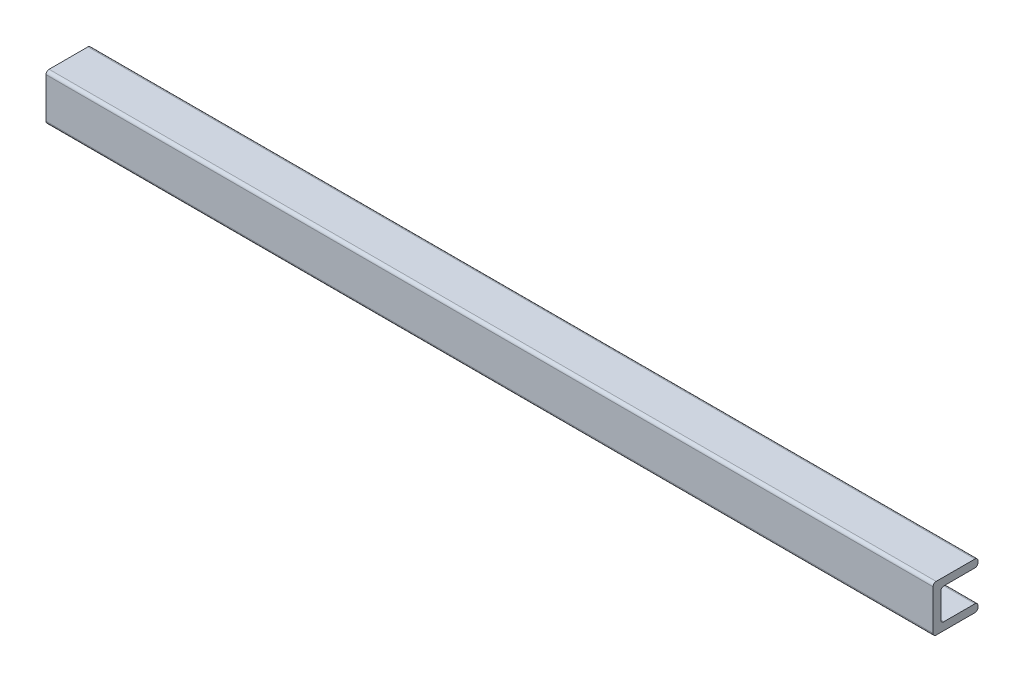
SolidWorks part; units mm, degrees
material "1023 Carbon Steel Sheet (SS)"
ref_plane "Ön Düzlem" through (0, 0, 0) normal (0, 0, 1) x (1, 0, 0)
ref_plane "Üst Düzlem" through (0, 0, 0) normal (0, 1, 0) x (1, 0, 0)
ref_plane "Sağ Düzlem" through (0, 0, 0) normal (1, 0, 0) x (0, 0, -1)
sketch "Sketch1" plane through (0, 0, 0) normal (1, 0, 0) x (0, 0, -1)
  line L0 (-168, 10) -> (-188, 10)
  line L1 (-190, 8) -> (-190, -8)
  line L2 (-188, -10) -> (-168, -10)
  line L3 (-168, 15) -> (-193, 15)
  line L4 (-195, 13) -> (-195, -13)
  line L5 (-193, -15) -> (-168, -15)
  line L6 (-166, 13) -> (-166, 12)
  line L7 (-166, -12) -> (-166, -13)
  line L8 (-177.3019, 10) -> (-190, 10) construction
  line L9 (-195, 15) -> (-195, -15) construction
  line L10 (-195, -15) -> (-166, -15) construction
  line L11 (-190, 10) -> (-190, -10) construction
  line L12 (-190, -10) -> (-166, -10) construction
  line L13 (-177.3019, 15) -> (-195, 15) construction
  arc A0 (-168, 10) -> (-166, 12) centre (-168, 12) ccw
  arc A1 (-195, -13) -> (-193, -15) centre (-193, -13) ccw
  arc A2 (-188, 10) -> (-190, 8) centre (-188, 8) ccw
  arc A3 (-190, -8) -> (-188, -10) centre (-188, -8) ccw
  arc A4 (-168, -10) -> (-166, -12) centre (-168, -12) cw
  arc A5 (-168, -15) -> (-166, -13) centre (-168, -13) ccw
  arc A6 (-168, 15) -> (-166, 13) centre (-168, 13) cw
  arc A7 (-193, 15) -> (-195, 13) centre (-193, 13) ccw
  point P6 (-190, 0)
  point P16 (-166, 10)
  dimension "D5" = 2
  dimension "D1" = 20
  dimension "D2" = 24
  dimension "D3" = 190
  dimension "D4" = 5
extrude "Boss-Extrude1" add sketch "Sketch1" along normal blind 572 from offset 30
ref_plane "Plane1" through (70, 0, 0) normal (-1, 0, 0) x (0, 0, 1)
sketch "Sketch2" plane through (0, 0, 190) normal (0, 0, -1) x (-1, 0, 0)
  line L0 (-70, 2.25) -> (-560, 2.25)
  line L1 (-70, -15.95) -> (-70, 15.95) construction
  line L2 (-70, -2.25) -> (-560, -2.25)
  line L3 (-602, -8) -> (-602, 8) construction
  line L4 (-602, -8) -> (-602, 8)
  line L5 (-1600, 0) -> (48400, 0) construction
  arc A0 (-560, 2.25) -> (-560, -2.25) centre (-560, 0) ccw
  arc A1 (-70, 2.25) -> (-70, -2.25) centre (-70, 0) cw
  point P8 (-602, 0)
  point P12 (-562.25, 0)
  point P13 (-67.75, 0)
  dimension "D1" = 490
  dimension "D2" = 4.5
extrude "Cut-Extrude1" cut sketch "Sketch2" against normal blind 4.5 contours A0 L5 A1 L0 | L5 A0 L2 A1
